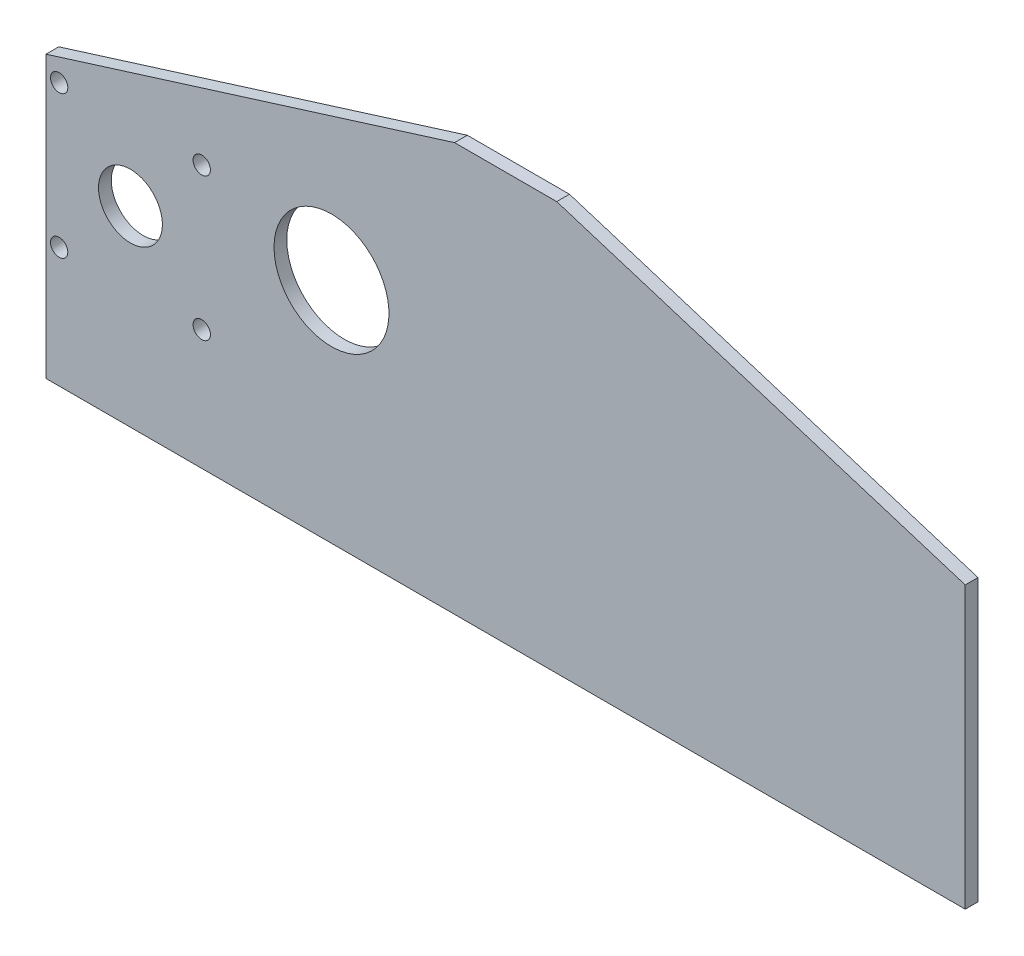
SolidWorks part; units mm, degrees
material "6061 Alloy"
ref_plane "Front" through (0, 0, 0) normal (0, 0, 1) x (1, 0, 0)
ref_plane "Top" through (0, 0, 0) normal (0, 1, 0) x (1, 0, 0)
ref_plane "Right" through (0, 0, 0) normal (1, 0, 0) x (0, 0, -1)
sketch "Sketch1" plane through (0, 0, 0) normal (0, 0, 1) x (1, 0, 0)
  line L0 (0, 101.6) -> (-101.6, 69.85)
  line L1 (-101.6, 69.85) -> (-101.6, 0)
  line L2 (-101.6, 0) -> (0, 0)
  line L3 (0, 0) -> (127, 0)
  line L4 (127, 0) -> (127, 69.85)
  line L5 (127, 69.85) -> (25.4, 101.6)
  line L6 (25.4, 101.6) -> (0, 101.6)
  dimension "D1" = 69.85
  dimension "D2" = 69.85
  dimension "D3" = 25.4
  dimension "D4" = 101.6
  dimension "D5" = 101.6
  dimension "D6" = 101.6
  dimension "D7" = 101.6
extrude "Boss-Extrude1" add sketch "Sketch1" along normal blind 3.175
sketch "Sketch5" plane through (0, 0, 0) normal (0, 0, -1) x (-1, 0, 0)
  line L0 (101.6, 69.85) -> (101.6, 0) construction
  circle A0 centre (80.6, 47.625) radius 7.9375
  dimension "D1" = 15.875
  dimension "D2" = 21
  dimension "D3" = 22.225
extrude "Cut-Extrude2" cut sketch "Sketch5" against normal through all
hole_wizard "#8 Clearance Hole2" positions "Sketch6" profile "Sketch7" hole size "#8" standard "ANSI Inch" end condition through all
sketch "Sketch6" plane through (0, 0, 0) normal (0, 0, -1) x (-1, 0, 0)
  line L5 (62.87, 65.355) -> (98.33, 65.355) construction
  line L6 (62.87, 65.355) -> (62.87, 29.895) construction
  line L7 (62.87, 29.895) -> (98.33, 29.895) construction
  line L8 (98.33, 65.355) -> (98.33, 29.895) construction
  line L9 (62.87, 65.355) -> (98.33, 29.895) construction
  line L10 (62.87, 29.895) -> (98.33, 65.355) construction
  point P14 (80.6, 47.625)
  point P15 (98.33, 29.895)
  point P80 (62.87, 65.355)
  point P81 (62.87, 29.895)
  point P82 (98.33, 65.355)
  dimension "D1" = 35.46
sketch "Sketch7" plane through (-80.6, 47.625, 0) normal (1, 0, 0) x (0, 1, 0)
  line L0 (0, 0) -> (0, 3.175)
  line L1 (0, 3.175) -> (2.1526, 3.175)
  line L2 (2.1526, 3.175) -> (2.1526, 0)
  line L5 (2.1526, 0) -> (0, 0)
  line L11 (0, -6.35) -> (0, 107.95) construction
  dimension "Thru Hole Dia." = 4.3053
  dimension "Thru Hole Depth" = 3.175
sketch "Sketch8" plane through (0, 0, 0) normal (0, 0, -1) x (-1, 0, 0)
  circle A0 centre (30.607, 56.6439) radius 14.2875
  circle A1 centre (80.6, 47.625) radius 7.9375 construction
  dimension "D1" = 28.575
  dimension "D2" = 30.607
  dimension "D3" = 50.8
extrude "Cut-Extrude3" cut sketch "Sketch8" against normal through all
